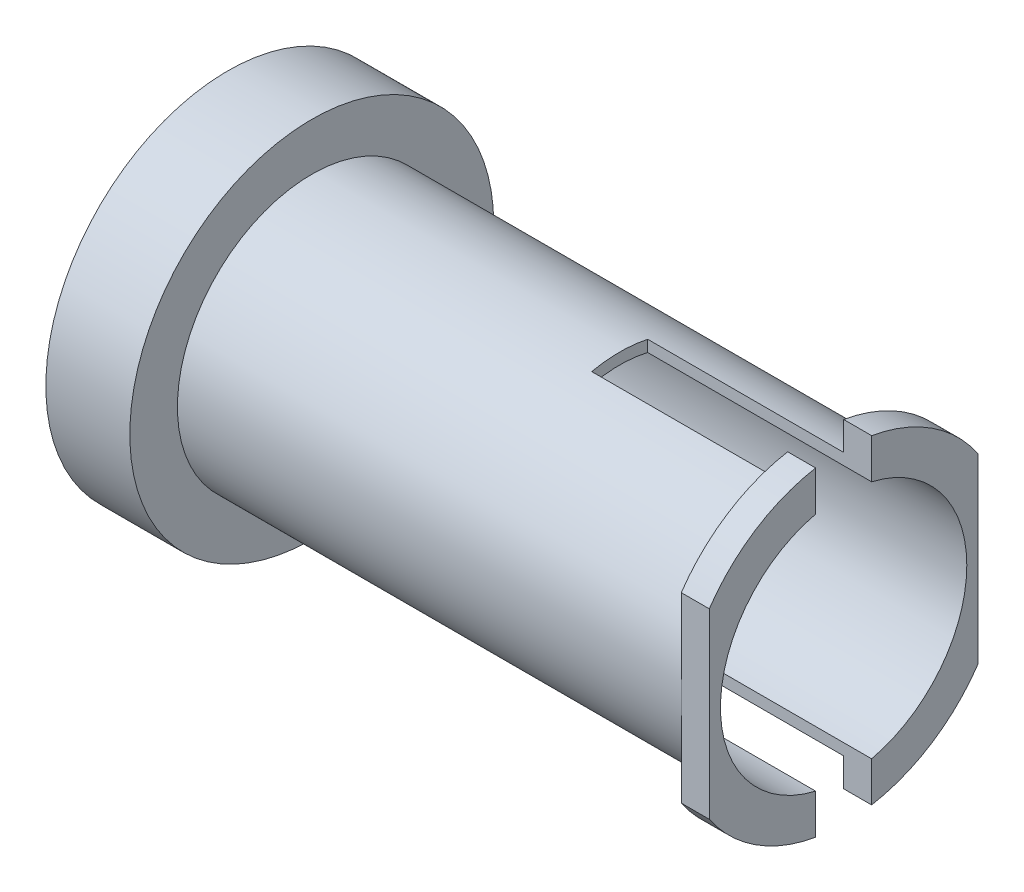
SolidWorks part; units mm, degrees
ref_plane "Front Plane" through (0, 0, 0) normal (0, 0, 1) x (1, 0, 0)
ref_plane "Top Plane" through (0, 0, 0) normal (0, 1, 0) x (1, 0, 0)
ref_plane "Right Plane" through (0, 0, 0) normal (1, 0, 0) x (0, 0, -1)
sketch "Sketch3" plane through (0, 0, 0) normal (0, 0, 1) x (1, 0, 0)
  line L0 (0, 0) -> (0, 3.25)
  line L1 (0, 3.25) -> (1.5, 3.25)
  line L2 (1.5, 3.25) -> (1.5, 2.4)
  line L3 (1.5, 2.4) -> (10.5, 2.4)
  line L4 (10.5, 2.4) -> (10.5, 2.9)
  line L5 (10.5, 2.9) -> (11, 2.9)
  line L6 (11, 2.9) -> (11, 0)
  line L7 (11, 0) -> (0, 0)
  dimension "D1" = 9
  dimension "D2" = 1.5
  dimension "D3" = 0.5
  dimension "D4" = 0.5
  dimension "D5" = 2.4
  dimension "D6" = 3.25
revolve "Revolve5" add sketch "Sketch3" angle 360 about L7
sketch "Sketch4" plane through (11, 0, 0) normal (1, 0, 0) x (0, 0, -1)
  line L1 (-0.5, -2.9) -> (0.5, -2.9)
  line L2 (-0.5, -2.9) -> (-0.5, 2.9)
  line L3 (-0.5, 2.9) -> (0.5, 2.9)
  line L4 (0.5, -2.9) -> (0.5, 2.9)
  line L5 (-2.9, 2.4) -> (-2.4, 2.4)
  line L6 (-2.9, 2.4) -> (-2.9, -2.4)
  line L7 (-2.9, -2.4) -> (-2.4, -2.4)
  line L8 (-2.4, 2.4) -> (-2.4, -2.4)
  line L9 (2.9, -2.4) -> (2.4, -2.4)
  line L10 (2.9, -2.4) -> (2.9, 2.1915)
  line L11 (2.9, 2.1915) -> (2.4, 2.1915)
  line L12 (2.4, -2.4) -> (2.4, 2.1915)
  circle A0 centre (0, 0) radius 2.9 construction
  circle A1 centre (0, 0) radius 3.25 construction
  circle A2 centre (0, 0) radius 2.2
  circle M5 centre (0, 0) radius 2.9
  dimension "D12" = 4.4
  dimension "D1" = 0.5
  dimension "D2" = 1
  dimension "D3" = 5.8
  dimension "D4" = 2.9
  dimension "D5" = 2.4
  dimension "D6" = 0.5
  dimension "D7" = 4.8
  dimension "D8" = 2.4
  dimension "D9" = 0.5
  dimension "D10" = 2.4
  dimension "D11" = 2.4
extrude "Cut-Extrude6" cut sketch "Sketch4" against normal blind 4 contours A2 L2 L4 M5 | L4 A2 L2 | A2 L4 L2 M5 | L2 A2 | L4 A2 | L12 M5 | L8 M5
sketch "Sketch5" plane through (7, 0, 0) normal (1, 0, 0) x (0, 0, -1)
  circle A0 centre (0, 0) radius 2.2
  dimension "D1" = 4.4
extrude "Cut-Extrude7" cut sketch "Sketch5" against normal blind 5.5
